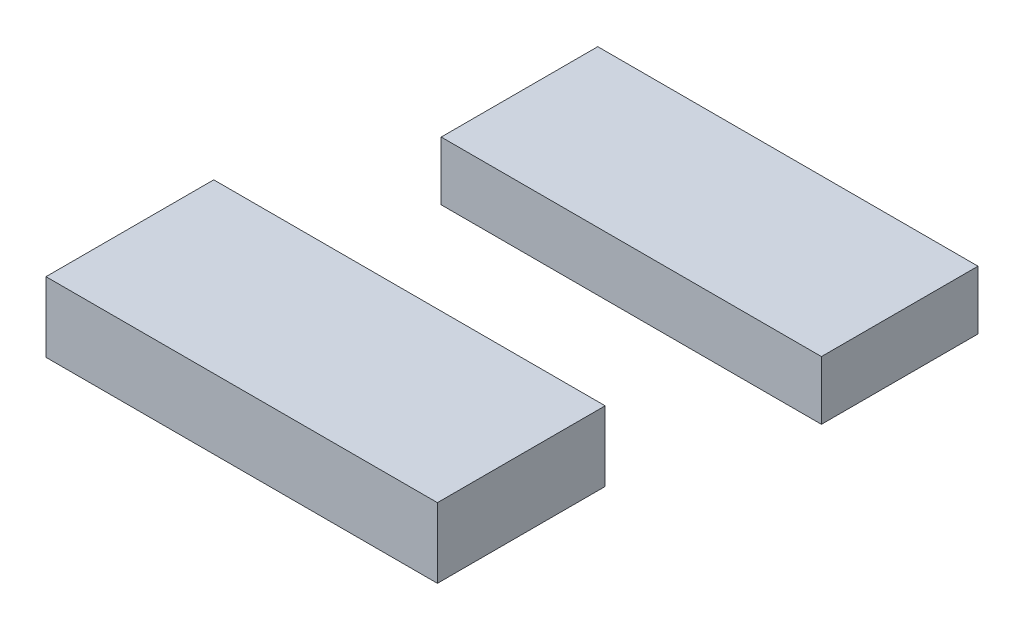
SolidWorks part; units mm, degrees
ref_plane "Front Plane" through (0, 0, 0) normal (0, 0, 1) x (1, 0, 0)
ref_plane "Top Plane" through (0, 0, 0) normal (0, 1, 0) x (1, 0, 0)
ref_plane "Right Plane" through (0, 0, 0) normal (1, 0, 0) x (0, 0, -1)
sketch "Sketch1" plane through (0, 0, 0) normal (0, 1, 0) x (1, 0, 0)
  line L1 (-23.6287, 13.9786) -> (-9.6287, 13.9786)
  line L2 (-23.6287, 13.9786) -> (-23.6287, 7.9786)
  line L3 (-23.6287, 7.9786) -> (-9.6287, 7.9786)
  line L4 (-9.6287, 13.9786) -> (-9.6287, 7.9786)
  line L5 (-23.6287, 13.9786) -> (-9.6287, 7.9786) construction
  line L6 (-23.6287, 7.9786) -> (-9.6287, 13.9786) construction
  point P0 (-16.6287, 10.9786)
  dimension "D1" = 14
  dimension "D2" = 6
extrude "Boss-Extrude1" add sketch "Sketch1" along normal blind 2.5
sketch "Sketch2" plane through (0, 0, 0) normal (0, 1, 0) x (1, 0, 0)
  line L1 (-21.2859, 19.7713) -> (-7.6859, 19.7713)
  line L2 (-21.2859, 19.7713) -> (-21.2859, 25.3713)
  line L3 (-21.2859, 25.3713) -> (-7.6859, 25.3713)
  line L4 (-7.6859, 19.7713) -> (-7.6859, 25.3713)
  dimension "D1" = 13.6
  dimension "D2" = 5.6
extrude "Boss-Extrude2" add sketch "Sketch2" along normal blind 2.1 separate body
